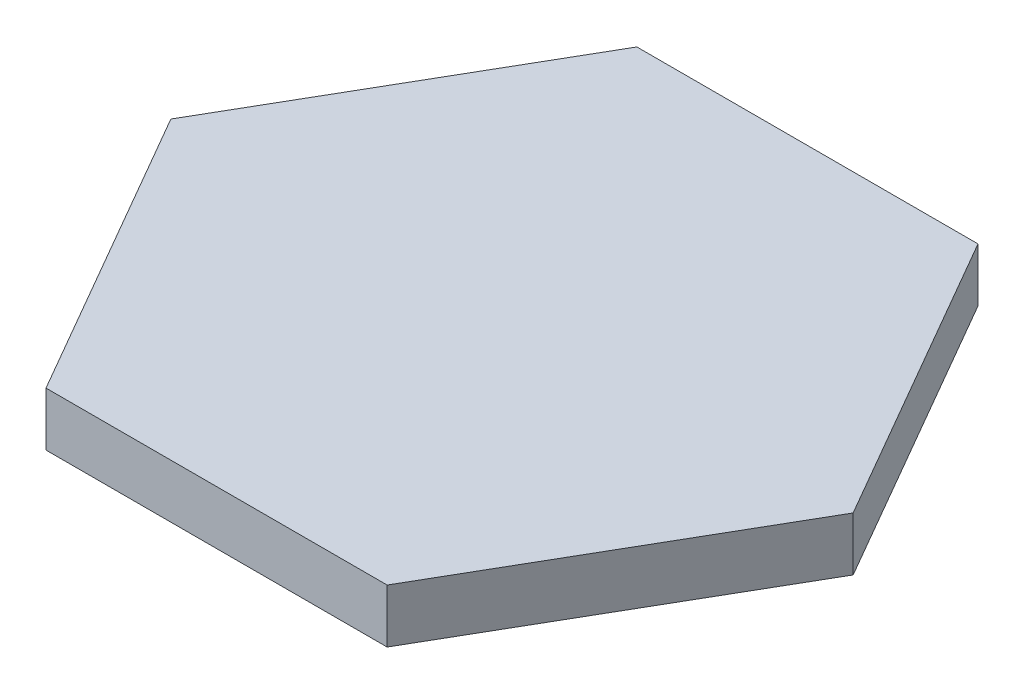
SolidWorks part; units mm, degrees
ref_plane "Front Plane" through (0, 0, 0) normal (0, 0, 1) x (1, 0, 0)
ref_plane "Top Plane" through (0, 0, 0) normal (0, 1, 0) x (1, 0, 0)
ref_plane "Right Plane" through (0, 0, 0) normal (1, 0, 0) x (0, 0, -1)
sketch "Sketch1" plane through (0, 0, 0) normal (0, 1, 0) x (1, 0, 0)
  line L0 (-17.6954, 0) -> (21.2766, 0) construction
  line L1 (40.3279, -69.85) -> (80.6558, 0)
  line L2 (80.6558, 0) -> (40.3279, 69.85)
  line L3 (40.3279, 69.85) -> (-40.3279, 69.85)
  line L4 (-40.3279, 69.85) -> (-80.6558, 0)
  line L5 (-80.6558, 0) -> (-40.3279, -69.85)
  line L6 (-40.3279, -69.85) -> (40.3279, -69.85)
  circle A0 centre (0, 0) radius 69.85 construction
  dimension "D1" = 139.7
extrude "Boss-Extrude1" add sketch "Sketch1" along normal blind 12.7
sketch "Sketch5" plane through (0, 12.7, 0) normal (0, 1, 0) x (1, 0, 0)
  circle A0 centre (0, 0) radius 22.1507
